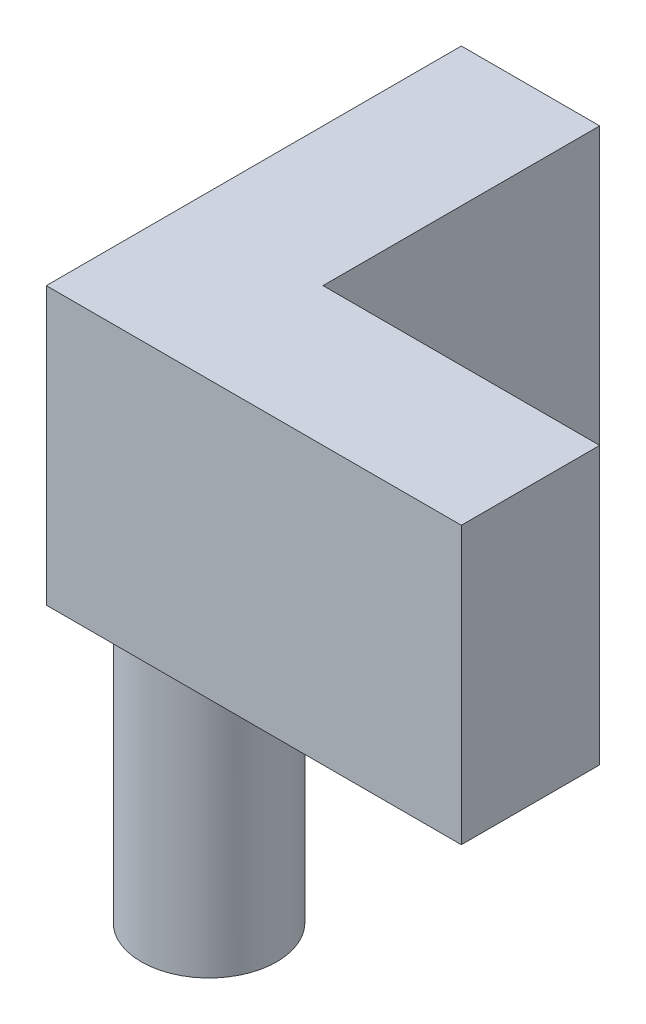
SolidWorks part; units mm, degrees
ref_plane "Front Plane" through (0, 0, 0) normal (0, 0, 1) x (1, 0, 0)
ref_plane "Top Plane" through (0, 0, 0) normal (0, 1, 0) x (1, 0, 0)
ref_plane "Right Plane" through (0, 0, 0) normal (1, 0, 0) x (0, 0, -1)
sketch "Sketch1" plane through (0, 0, 0) normal (0, 1, 0) x (1, 0, 0)
  line L0 (0, 15) -> (0, 0)
  line L3 (0, 15) -> (5, 15)
  line L4 (5, 5) -> (5, 15)
  line L7 (5, 5) -> (15, 5)
  line L8 (15, 0) -> (15, 5)
  line L9 (0, 0) -> (15, 0)
  circle A0 centre (2.8799, 3.0008) radius 2.5
  dimension "D4" = 5
  dimension "D1" = 15
  dimension "D2" = 15
  dimension "D3" = 5
extrude "Boss-Extrude1" add sketch "Sketch1" along normal blind 10
sketch "Sketch2" plane through (0, 10, 0) normal (0, 1, 0) x (1, 0, 0)
  circle A0 centre (2.8799, 3.0008) radius 2.45
  dimension "D1" = 4.9
extrude "Boss-Extrude2" add sketch "Sketch2" against normal blind 20
sketch "Sketch3" plane through (0, 10, 0) normal (0, 1, 0) x (1, 0, 0)
  circle A0 centre (2.8799, 3.0008) radius 2.5
  circle A1 centre (2.8799, 3.0008) radius 2.5 construction
  dimension "D1" = 0
  dimension "D2" = 5
extrude "Boss-Extrude3" add sketch "Sketch3" against normal blind 10
